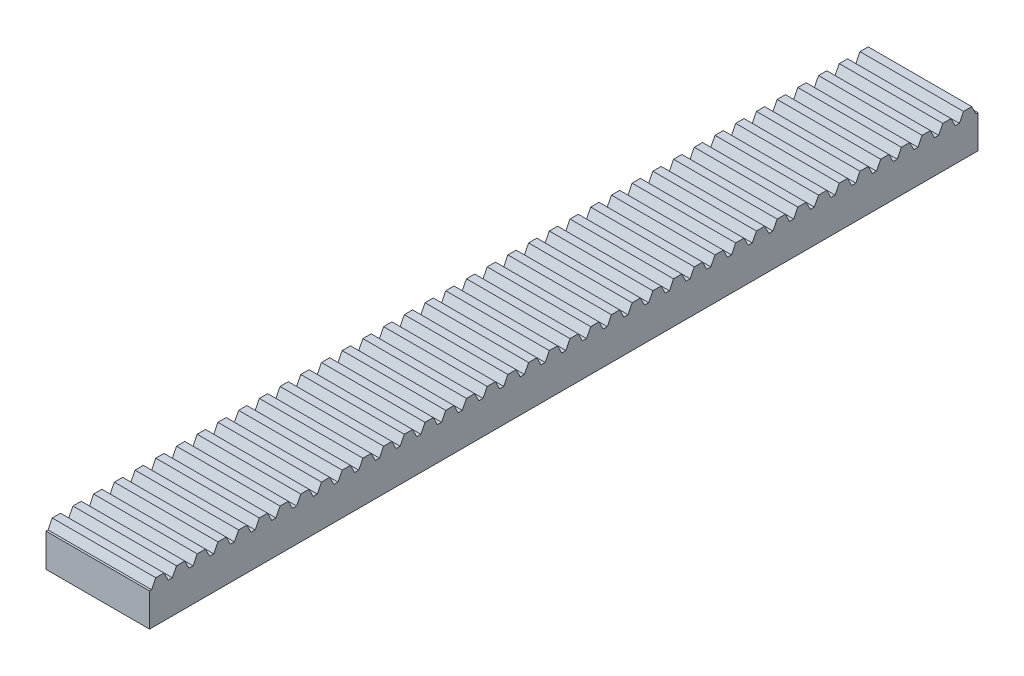
SolidWorks part; units mm, degrees
ref_plane "Front Plane" through (0, 0, 0) normal (0, 0, 1) x (1, 0, 0)
ref_plane "Top Plane" through (0, 0, 0) normal (0, 1, 0) x (1, 0, 0)
ref_plane "Right Plane" through (0, 0, 0) normal (1, 0, 0) x (0, 0, -1)
sketch "Sketch1" plane through (0, 0, 0) normal (0, 0, 1) x (1, 0, 0)
  line L0 (-25, 0) -> (25, 0)
  line L1 (25, 0) -> (25, 20)
  line L2 (25, 20) -> (-25, 20)
  line L3 (-25, 20) -> (-25, 0)
  point P4 (0, 0)
  dimension "D1" = 20
  dimension "D2" = 50
extrude "Boss-Extrude1" add sketch "Sketch1" along normal blind 400
sketch "Sketch2" plane through (25, 0, 0) normal (1, 0, 0) x (0, 0, -1)
  line L0 (-403, 20) -> (-397, 20)
  line L2 (-400, 20) -> (0, 20) construction
  line L3 (-397, 20) -> (-399, 16)
  line L4 (-399, 16) -> (-401, 16)
  line L5 (-401, 16) -> (-403, 20)
  point P0 (-399.1582, 16)
  point P4 (-400, 20)
  point P10 (-400, 16)
  dimension "D1" = 4
  dimension "D2" = 2
  dimension "D3" = 6
extrude "Cut-Extrude1" cut sketch "Sketch2" against normal up to next
pattern_linear "LPattern1" count 41 spacing 10 along (0, 0, -1) of "Cut-Extrude1"
